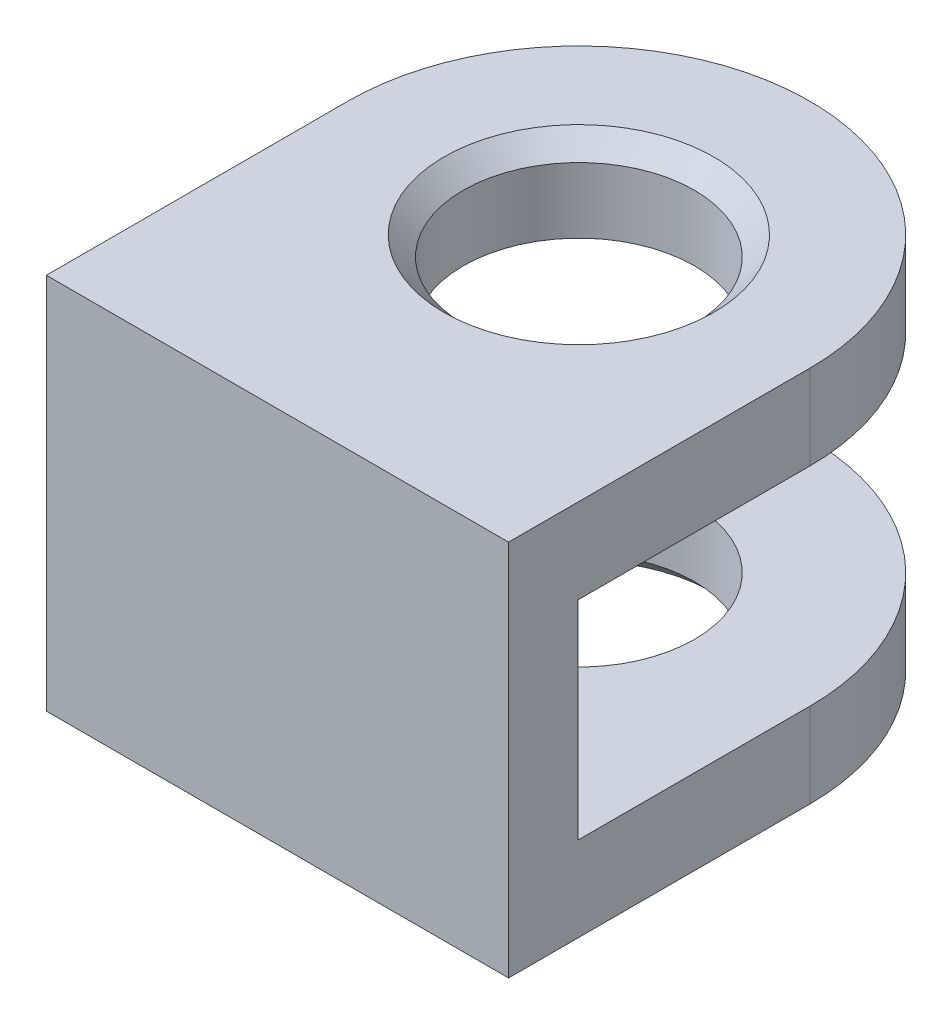
SolidWorks part; units mm, degrees
ref_plane "Front Plane" through (0, 0, 0) normal (0, 0, 1) x (1, 0, 0)
ref_plane "Top Plane" through (0, 0, 0) normal (0, 1, 0) x (1, 0, 0)
ref_plane "Right Plane" through (0, 0, 0) normal (1, 0, 0) x (0, 0, -1)
sketch "Sketch1" plane through (0, 0, 0) normal (0, 1, 0) x (1, 0, 0)
  line L0 (-6, 7.825) -> (-6, 0)
  line L1 (-6, 0) -> (6, 0)
  line L2 (6, 0) -> (6, 7.825)
  circle A0 centre (0, 7.825) radius 3
  arc A1 (6, 7.825) -> (-6, 7.825) centre (0, 7.825) ccw
  circle A2 centre (0, 7.825) radius 6 construction
  dimension "D1" = 6
  dimension "D2" = 7.825
  dimension "D3" = 3
extrude "Boss-Extrude1" add sketch "Sketch1" along normal mid plane 9.8
sketch "Sketch3" plane through (0, 0, 0) normal (0, 1, 0) x (1, 0, 0)
  line L0 (6, 1.8) -> (-6, 1.8)
  line L1 (-6, 0) -> (6, 0) construction
  line L3 (-6, 7.825) -> (-6, 0)
  line L4 (-6, 0) -> (6, 0)
  line L5 (6, 0) -> (6, 7.825)
  line L6 (-6, 7.825) -> (-6, 1.8)
  line L8 (6, 1.8) -> (6, 7.825)
  arc A1 (6, 7.825) -> (-6, 7.825) centre (0, 7.825) ccw
  arc A2 (6, 7.825) -> (-6, 7.825) centre (0, 7.825) ccw
  dimension "D1" = 0
  dimension "D2" = 1.8
extrude "Cut-Extrude1" cut sketch "Sketch3" against normal mid plane 5.4
chamfer "Chamfer1" distance 0.5 angle 45 2 edges at (0, 4.9, -4.825) (0, -4.9, -4.825)
